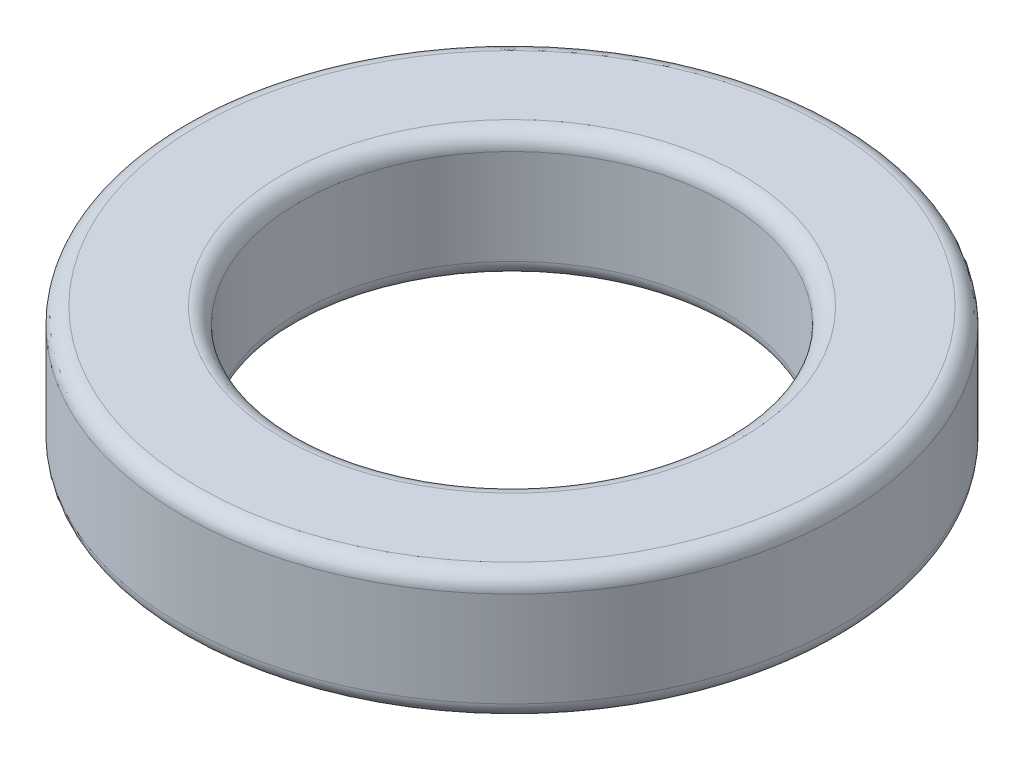
SolidWorks part; units mm, degrees
ref_plane "Front Plane" through (0, 0, 0) normal (0, 0, 1) x (1, 0, 0)
ref_plane "Top Plane" through (0, 0, 0) normal (0, 1, 0) x (1, 0, 0)
ref_plane "Right Plane" through (0, 0, 0) normal (1, 0, 0) x (0, 0, -1)
sketch "Sketch1" plane through (0, 0, 0) normal (0, 1, 0) x (1, 0, 0)
  circle A0 centre (0, 0) radius 31
  circle A1 centre (0, 0) radius 20
  dimension "D1" = 40
  dimension "D2" = 62
extrude "Boss-Extrude1" add sketch "Sketch1" along normal mid plane 12
fillet "Fillet1" radius 1.524 4 edges at (0, -6, 31) (0, -6, 20) (0, 6, 20) (0, 6, 31)
